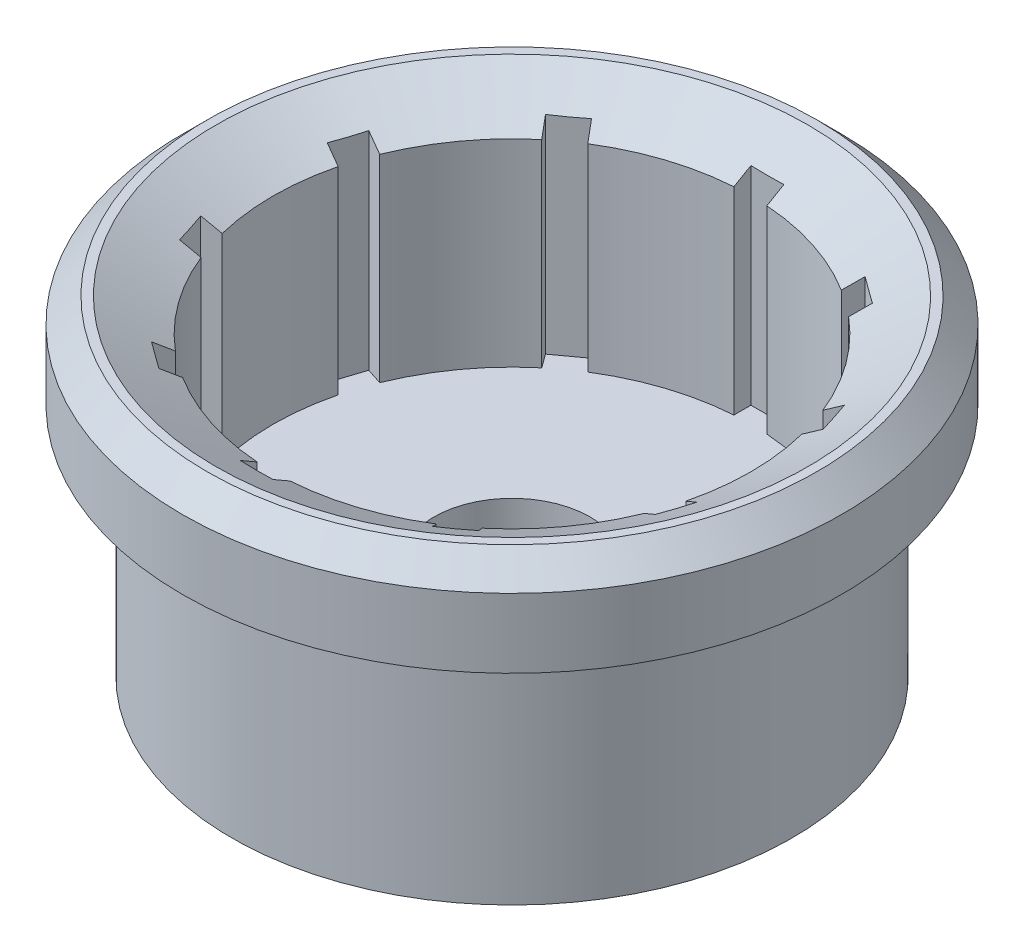
SolidWorks part; units mm, degrees
ref_plane "前视基准面" through (0, 0, 0) normal (0, 0, 1) x (1, 0, 0)
ref_plane "上视基准面" through (0, 0, 0) normal (0, 1, 0) x (1, 0, 0)
ref_plane "右视基准面" through (0, 0, 0) normal (1, 0, 0) x (0, 0, -1)
sketch "草图1" plane through (0, 0, 0) normal (0, 0, 1) x (1, 0, 0)
  line L0 (0, 0) -> (-4.4767, 0) construction
  line L1 (0, 0) -> (0, 28.0423) construction
  line L2 (-2.5, 0) -> (-2.5, 8)
  line L3 (-2.5, 8) -> (-4.75, 8)
  line L4 (-4.75, 8) -> (-4.75, 12)
  line L5 (-4.75, 12) -> (-14.5, 12)
  line L6 (-14.5, 12) -> (-14.5, 26)
  line L7 (-14.5, 26) -> (-20, 26)
  line L8 (-20, 26) -> (-20, 20.3)
  line L9 (-20, 20.3) -> (-17, 20.3)
  line L10 (-17, 20.3) -> (-17, 6)
  line L11 (-17, 6) -> (-6.5, 6)
  line L12 (-6.5, 6) -> (-6.5, 5)
  line L13 (-6.5, 5) -> (-4.5, 5)
  line L14 (-4.5, 5) -> (-4.5, 0)
  line L15 (-4.5, 0) -> (-2.5, 0)
  dimension "D1" = 5
  dimension "D2" = 9
  dimension "D3" = 2
  dimension "D4" = 6
  dimension "D5" = 3
  dimension "D6" = 9.5
  dimension "D7" = 4
  dimension "D8" = 1
  dimension "D9" = 34
  dimension "D10" = 40
  dimension "D11" = 5.7
  dimension "D12" = 29
  dimension "D13" = 14
revolve "旋转1" add sketch "草图1" angle 360 about L1
chamfer "倒角1" distance 2 angle 60 1 edges at (0, 26, -14.5)
chamfer "倒角2" distance 1.5 angle 45 1 edges at (0, 26, -20)
sketch "草图2" plane through (0, 12, 0) normal (0, 1, 0) x (1, 0, 0)
  line L1 (1, -15.5) -> (-1, -15.5)
  line L2 (1, -15.5) -> (1, 15.5)
  line L3 (1, 15.5) -> (-1, 15.5)
  line L4 (-1, -15.5) -> (-1, 15.5)
  line L5 (1, -15.5) -> (-1, 15.5) construction
  line L6 (1, 15.5) -> (-1, -15.5) construction
  point P5 (0, 0)
  dimension "D1" = 2
  dimension "D2" = 31
extrude "切除-拉伸1" cut sketch "草图2" along normal through all
pattern_circular "阵列(圆周)1" count 10 over 360 about axis through (0, 0, 0) along (0, 1, 0) of "切除-拉伸1"
